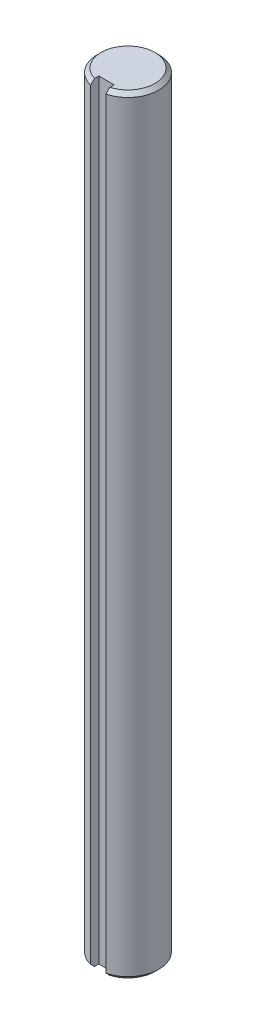
SolidWorks part; units mm, degrees
ref_plane "Top Plane" through (0, 0, 0) normal (0, 0, 1) x (1, 0, 0)
ref_plane "Front Plane" through (0, 0, 0) normal (0, 1, 0) x (1, 0, 0)
ref_plane "Right Plane" through (0, 0, 0) normal (1, 0, 0) x (0, 0, -1)
sketch "Sketch1" plane through (0, 0, 0) normal (0, 1, 0) x (1, 0, 0)
  circle A1 centre (0, 0) radius 4
  dimension "D1" = 8
extrude "Boss-Extrude1" add sketch "Sketch1" along normal blind 100
sketch "Sketch2" plane through (0, 0, 0) normal (0, -1, 0) x (1, 0, 0)
  line L1 (-1, 2.8) -> (1, 2.8)
  line L2 (-1, 2.8) -> (-1, 4.8)
  line L3 (-1, 4.8) -> (1, 4.8)
  line L4 (1, 2.8) -> (1, 4.8)
  circle A0 centre (0, 0) radius 4 construction
  point P4 (0, 2.8)
  dimension "D2" = 1.2
  dimension "D1" = 2
  dimension "D3" = 2
extrude "Cut-Extrude1" cut sketch "Sketch2" against normal through all
chamfer "Chamfer1" distance 0.5 angle 45 2 edges at (0, 100, -4) (0, 0, -4)
equation "\"D1@Boss-Extrude1\"=100mm"
